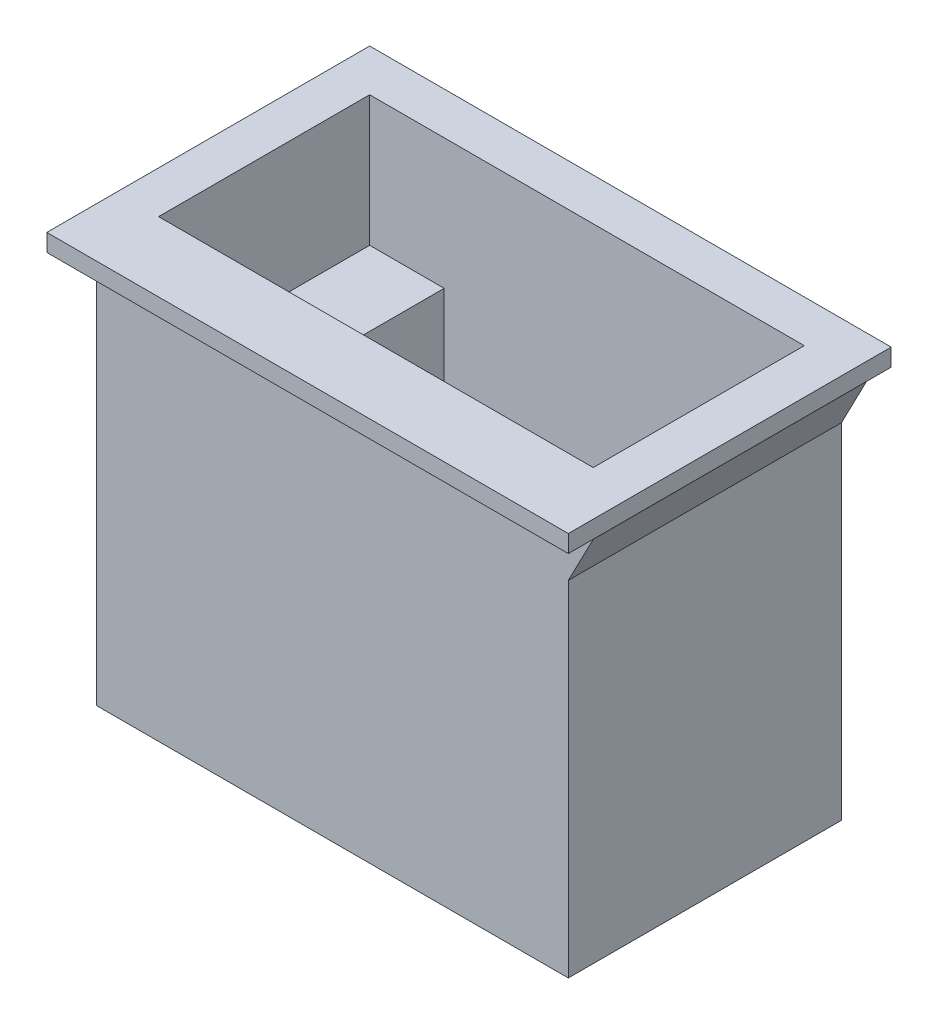
SolidWorks part; units mm, degrees
ref_plane "Front Plane" through (0, 0, 0) normal (0, 0, 1) x (1, 0, 0)
ref_plane "Top Plane" through (0, 0, 0) normal (0, 1, 0) x (1, 0, 0)
ref_plane "Right Plane" through (0, 0, 0) normal (1, 0, 0) x (0, 0, -1)
sketch "Sketch1" plane through (0, 0, 0) normal (0, 1, 0) x (1, 0, 0)
  line L0 (8.6, 5.9429) -> (8.6, -20.9814) construction
  line L1 (-10.4, 5.9429) -> (27.6, 5.9429)
  line L2 (-10.4, 5.9429) -> (-10.4, -16.0571)
  line L3 (-10.4, -16.0571) -> (27.6, -16.0571)
  line L4 (27.6, 5.9429) -> (27.6, -16.0571)
  dimension "D1" = 38
  dimension "D2" = 22
extrude "Boss-Extrude1" add sketch "Sketch1" along normal blind 33
sketch "Sketch2" plane through (0, 33, 0) normal (0, 1, 0) x (1, 0, 0)
  line L0 (27.6, 5.9429) -> (-10.4, 5.9429) construction
  line L1 (-9, 4.5429) -> (26, 4.5429)
  line L2 (-9, 4.5429) -> (-9, -12.4571)
  line L3 (-9, -12.4571) -> (26, -12.4571)
  line L4 (26, 4.5429) -> (26, -12.4571)
  line L5 (-10.4, 5.9429) -> (-10.4, -16.0571) construction
  dimension "D1" = 35
  dimension "D2" = 17
  dimension "D3" = 1.4
  dimension "D4" = 1.4
extrude "Cut-Extrude1" cut sketch "Sketch2" against normal blind 28
sketch "Sketch3" plane through (0, 5, 0) normal (0, 1, 0) x (1, 0, 0)
  line L0 (-9, -12.4571) -> (26, -12.4571) construction
  line L1 (-9, 4.5429) -> (-3, 4.5429)
  line L2 (-9, 4.5429) -> (-9, -12.4571)
  line L3 (-9, -12.4571) -> (-3, -12.4571)
  line L4 (-3, 4.5429) -> (-3, -12.4571)
  line L5 (26, 4.5429) -> (-9, 4.5429) construction
  line L6 (20, 4.5429) -> (26, 4.5429)
  line L7 (20, 4.5429) -> (20, -12.4571)
  line L8 (20, -12.4571) -> (26, -12.4571)
  line L9 (26, 4.5429) -> (26, -12.4571)
  dimension "D1" = 6
  dimension "D2" = 6
extrude "Boss-Extrude2" add sketch "Sketch3" along normal blind 17.5
sketch "Sketch4" plane through (0, 33, 0) normal (0, 1, 0) x (1, 0, 0)
  line L1 (-10.4, 5.9429) -> (27.6, 5.9429)
  line L2 (-10.4, 5.9429) -> (-10.4, -16.0571)
  line L3 (-10.4, -16.0571) -> (27.6, -16.0571)
  line L4 (27.6, 5.9429) -> (27.6, -16.0571)
extrude "Extrude-Thin2" add sketch "Sketch4" against normal blind 1.4 thin thin type one direction wall 2
sketch "Sketch5" plane through (0, 22.5, 0) normal (0, 1, 0) x (1, 0, 0)
  line L0 (-3, -12.4571) -> (-3, 4.5429) construction
  circle A0 centre (-5.5, -3.8921) radius 1
  dimension "D1" = 2
  dimension "D2" = 2.5
extrude "Cut-Extrude2" cut sketch "Sketch5" against normal blind 3
sketch "Sketch6" plane through (0, 22.5, 0) normal (0, 1, 0) x (1, 0, 0)
  circle A0 centre (22.9531, -4.1157) radius 1
  dimension "D1" = 2
extrude "Cut-Extrude3" cut sketch "Sketch6" against normal blind 3
sketch "Sketch7" plane through (-3, 0, 0) normal (1, 0, 0) x (0, 0, -1)
  line L0 (5.9429, 31.6) -> (5.9429, 0) construction
  line L1 (0.9429, 4.0414) -> (-8.4571, 4.0414)
  line L2 (0.9429, 4.0414) -> (0.9429, 8.5414)
  line L3 (0.9429, 8.5414) -> (-8.4571, 8.5414)
  line L4 (-8.4571, 4.0414) -> (-8.4571, 8.5414)
  point P4 (0.9429, 6.2914)
  dimension "D1" = 9.4
  dimension "D2" = 4.5
  dimension "D3" = 5
extrude "Cut-Extrude4" cut sketch "Sketch7" against normal blind 10
sketch "Sketch8" plane through (0, 5, 0) normal (0, 1, 0) x (1, 0, 0)
  line L1 (-1.4079, -8.7279) -> (18.5921, -8.7279)
  line L2 (-1.4079, -8.7279) -> (-1.4079, 1.2721)
  line L3 (-1.4079, 1.2721) -> (18.5921, 1.2721)
  line L4 (18.5921, -8.7279) -> (18.5921, 1.2721)
  dimension "D1" = 10
  dimension "D2" = 20
extrude "Cut-Extrude5" cut sketch "Sketch8" against normal blind 1.5
sketch "Sketch9" plane through (0, 3.5, 0) normal (0, 1, 0) x (1, 0, 0)
  circle A0 centre (8.8083, -3.6349) radius 3.7
  circle A3 centre (1.6083, -3.6349) radius 1
  circle A4 centre (16.0083, -3.6349) radius 1
  dimension "D1" = 7.4
  dimension "D2" = 3.5
  dimension "D5" = 2
  dimension "D4" = 2
  dimension "D3" = 3.5
extrude "Cut-Extrude6" cut sketch "Sketch9" against normal blind 1.7
fillet "Fillet1" radius 4 4 edges at (18.5921, 4.25, -1.2721) (18.5921, 4.25, 8.7279) (-1.4079, 4.25, -1.2721) (-1.4079, 4.25, 8.7279)
sketch "Sketch10" plane through (0, 0, 16.0571) normal (0, 0, 1) x (1, 0, 0)
  line L0 (27.6, 31.6) -> (29.6074, 31.6)
  line L1 (29.6074, 31.6) -> (27.6, 27.7328)
  line L2 (27.6, 31.6) -> (27.6, 0) construction
  line L3 (27.6, 27.7328) -> (27.6, 31.6)
extrude "Boss-Extrude3" add sketch "Sketch10" against normal up to vertex
fillet "Fillet2" radius 3 1 edges at (-3, 8.5414, 3.7571)
